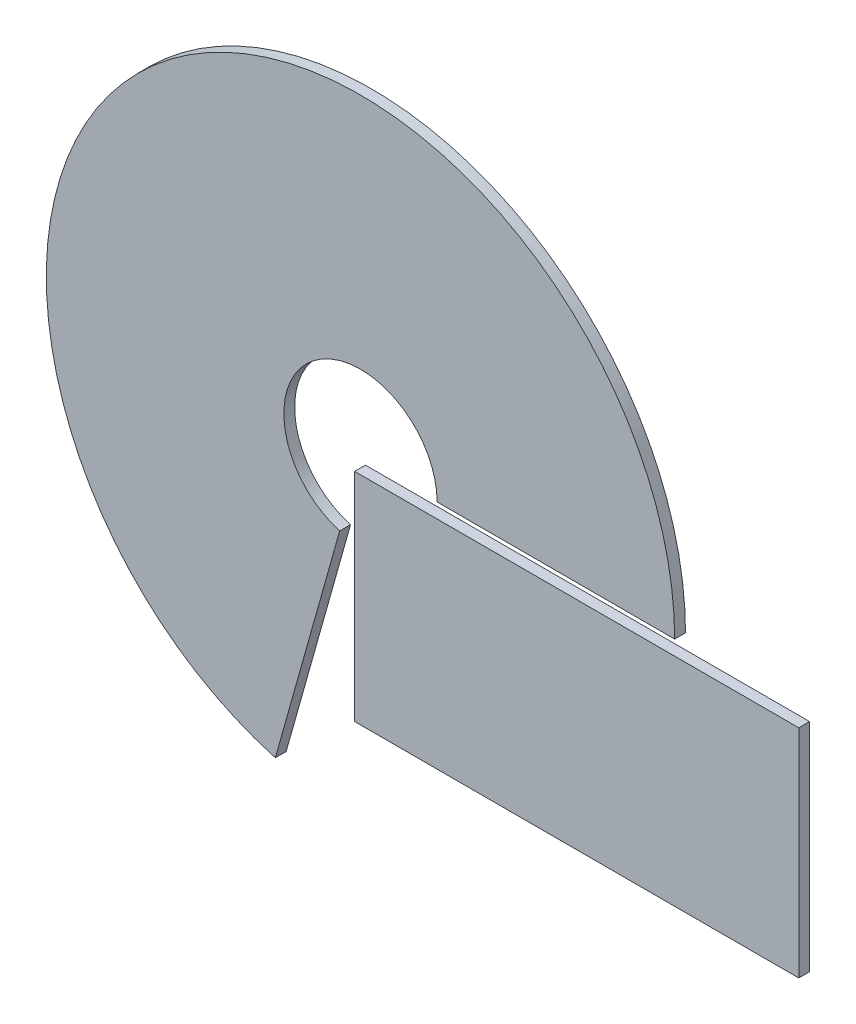
SolidWorks part; units mm, degrees
ref_plane "Front Plane" through (0, 0, 0) normal (0, 0, 1) x (1, 0, 0)
ref_plane "Top Plane" through (0, 0, 0) normal (0, 1, 0) x (1, 0, 0)
ref_plane "Right Plane" through (0, 0, 0) normal (1, 0, 0) x (0, 0, -1)
sketch "Sketch2" plane through (0, 0, 0) normal (0, 0, 1) x (1, 0, 0)
  line L0 (17.9714, 0) -> (73.66, 0)
  line L1 (-19.9637, -70.9031) -> (-4.8707, -17.2988)
  line L2 (-4.8707, -17.2988) -> (0, 0) construction
  line L4 (-1.3792, -54.2567) -> (102.7608, -54.2567)
  line L5 (-1.3792, -54.2567) -> (-1.3792, -3.4567)
  line L6 (-1.3792, -3.4567) -> (102.7608, -3.4567)
  line L7 (102.7608, -54.2567) -> (102.7608, -3.4567)
  arc A0 (-4.8707, -17.2988) -> (17.9714, 0) centre (0, 0) cw
  arc A1 (-19.9637, -70.9031) -> (73.66, 0) centre (0, 0) cw
  dimension "D1" = 73.66
  dimension "D2" = 326.898
  dimension "D3" = 79.756
  dimension "D4" = 50.8
  dimension "D5" = 104.14
extrude "Boss-Extrude1" add sketch "Sketch2" along normal blind 2.54
